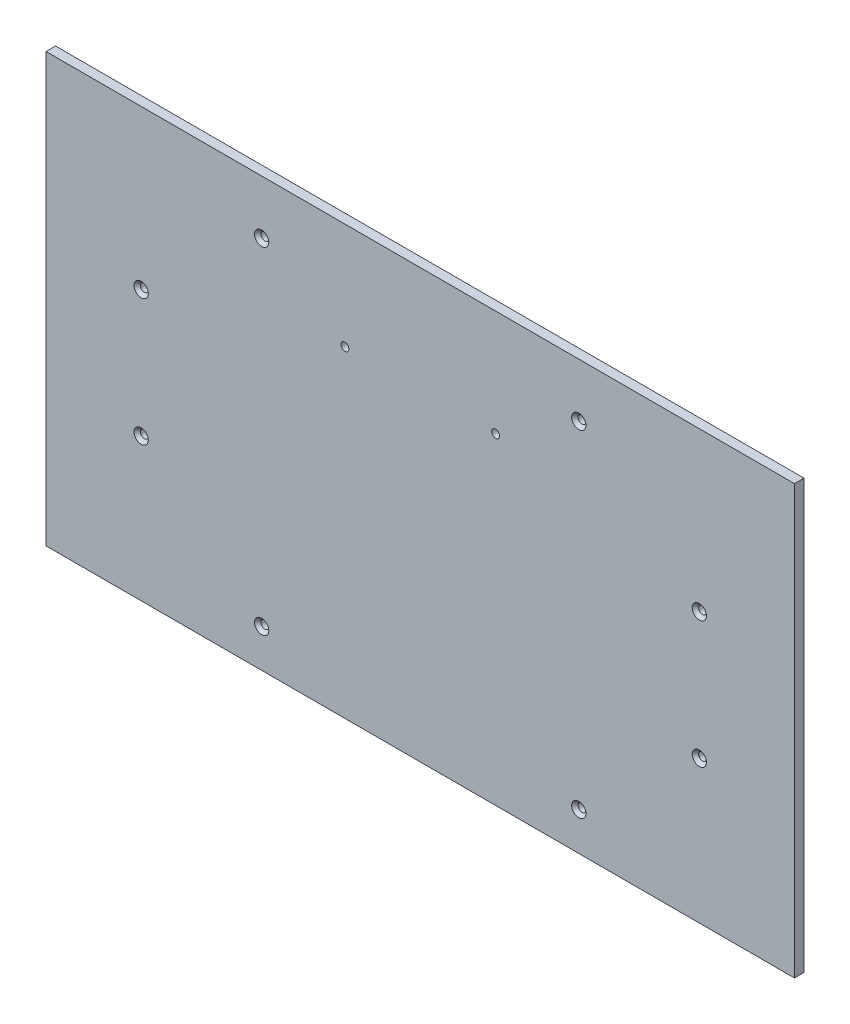
SolidWorks part; units mm, degrees
ref_plane "Plan de face" through (0, 0, 0) normal (0, 0, 1) x (1, 0, 0)
ref_plane "Plan de dessus" through (0, 0, 0) normal (0, 1, 0) x (1, 0, 0)
ref_plane "Plan de droite" through (0, 0, 0) normal (1, 0, 0) x (0, 0, -1)
sketch "Esquisse1" plane through (0, 0, 0) normal (0, 0, 1) x (1, 0, 0)
  line L1 (-236, -135) -> (236, -135)
  line L2 (-236, -135) -> (-236, 135)
  line L3 (-236, 135) -> (236, 135)
  line L4 (236, -135) -> (236, 135)
  line L5 (-236, -135) -> (236, 135) construction
  line L6 (-236, 135) -> (236, -135) construction
  point P0 (0, 0)
  dimension "D1" = 270
  dimension "D2" = 472
extrude "Boss.-Extru.1" add sketch "Esquisse1" along normal blind 6
sketch "Esquisse2" plane through (0, 0, 6) normal (0, 0, 1) x (1, 0, 0)
  line L0 (-236, 135) -> (-236, -135) construction
  line L1 (-176, -111) -> (176, -111) construction
  line L2 (-176, -111) -> (-176, 101) construction
  line L3 (-176, 101) -> (176, 101) construction
  line L4 (176, -111) -> (176, 101) construction
  line L5 (-176, -111) -> (176, 101) construction
  line L6 (-176, 101) -> (176, -111) construction
  line L7 (-236, -135) -> (236, -135) construction
  line L8 (236, 135) -> (-236, 135) construction
  line L9 (236, -135) -> (236, 135) construction
  line L10 (0, 135) -> (0, -135) construction
  line L11 (-234, -5) -> (234, -5) construction
  circle A0 centre (-100, 101) radius 2.5
  circle A1 centre (100, 101) radius 2.5
  circle A2 centre (176, 35) radius 2.5
  circle A3 centre (176, -45) radius 2.5
  circle A4 centre (100, -111) radius 2.5
  circle A5 centre (-100, -111) radius 2.5
  circle A6 centre (-176, -45) radius 2.5
  circle A7 centre (-176, 35) radius 2.5
  point P0 (0, -5)
  dimension "D5" = 5
  dimension "D1" = 60
  dimension "D2" = 24
  dimension "D3" = 34
  dimension "D4" = 60
  dimension "D6" = 200
  dimension "D7" = 80
extrude "Enlèv. mat.-Extru.1" cut sketch "Esquisse2" against normal through all
chamfer "Chanfrein1" distance 2 angle 45 8 edges at (-173.5, 35, 6) (-173.5, -45, 6) (-97.5, -111, 6) (102.5, -111, 6) (178.5, -45, 6) (178.5, 35, 6) (102.5, 101, 6) (-97.5, 101, 6)
sketch "Esquisse3" plane through (0, 0, 6) normal (0, 0, 1) x (1, 0, 0)
  line L0 (-47.5, 68) -> (47.5, 68) construction
  line L1 (236, 135) -> (-236, 135) construction
  circle A0 centre (-47.5, 68) radius 2.5
  circle A1 centre (47.5, 68) radius 2.5
  point P2 (0, 68)
  dimension "D3" = 5
  dimension "D1" = 67
  dimension "D2" = 95
extrude "Enlèv. mat.-Extru.2" cut sketch "Esquisse3" against normal through all
